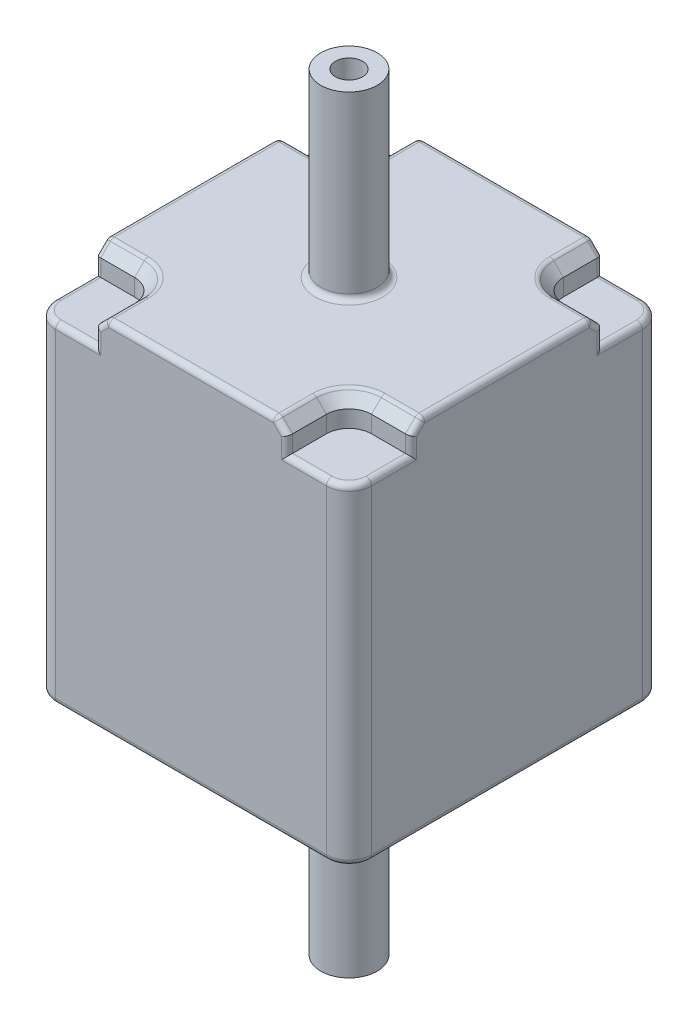
SolidWorks part; units mm, degrees
ref_plane "前视基准面" through (0, 0, 0) normal (0, 0, 1) x (1, 0, 0)
ref_plane "上视基准面" through (0, 0, 0) normal (0, 1, 0) x (1, 0, 0)
ref_plane "右视基准面" through (0, 0, 0) normal (1, 0, 0) x (0, 0, -1)
sketch "草图1" plane through (0, 0, 0) normal (0, 1, 0) x (1, 0, 0)
  line L1 (-14, 14) -> (14, 14)
  line L2 (-14, 14) -> (-14, -14)
  line L3 (-14, -14) -> (14, -14)
  line L4 (14, 14) -> (14, -14)
  point P4 (-14, 0)
  point P6 (0, 14)
  dimension "D1" = 28
  dimension "D2" = 28
extrude "凸台-拉伸1" add sketch "草图1" along normal blind 31.8
sketch "草图2" plane through (0, 0, 0) normal (0, -1, 0) x (-1, 0, 0)
  circle A0 centre (0, 0) radius 10.975
  dimension "D1" = 21.95
extrude "凸台-拉伸2" add sketch "草图2" along normal blind 2
sketch "草图3" plane through (0, -2, 0) normal (0, -1, 0) x (1, 0, 0)
  circle A0 centre (0, 0) radius 2.5
  dimension "D1" = 5
extrude "凸台-拉伸3" add sketch "草图3" along normal blind 18.2
sketch "草图4" plane through (0, 31.8, 0) normal (0, 1, 0) x (1, 0, 0)
  circle A0 centre (0, 0) radius 2.5
  dimension "D1" = 5
extrude "凸台-拉伸4" add sketch "草图4" along normal blind 16
fillet "圆角1" radius 2 4 edges at (14, 15.9, -14) (14, 15.9, 14) (-14, 15.9, -14) (-14, 15.9, 14)
sketch "草图5" plane through (0, 0, 0) normal (0, -1, 0) x (1, 0, 0)
  line L0 (-11.5, 11.5) -> (11.5, -11.5) construction
  circle A0 centre (-11.5, 11.5) radius 1.25
  circle A1 centre (11.5, 11.5) radius 1.25
  circle A2 centre (11.5, -11.5) radius 1.25
  circle A3 centre (-11.5, -11.5) radius 1.25
  point P8 (0, 0)
  point P9 (-14, -11.7456)
  point P11 (-7.5658, -11.5)
  point P12 (0, 0)
  point P13 (0, 0)
  point P14 (0, 0)
  point P15 (-14, -14)
  point P16 (9, 11.2897)
  point P17 (0, 0)
  point P18 (0, 0)
  dimension "D1" = 2.5
  dimension "D2" = 23
  dimension "D3" = 23
extrude "切除-拉伸1" cut sketch "草图5" against normal blind 5
sketch "草图6" plane through (0, 31.8, 0) normal (0, 1, 0) x (1, 0, 0)
  line L0 (-14, 12) -> (-14, -12) construction
  line L1 (-14, -8.5) -> (-10.5, -8.5)
  line L2 (-14, -8.5) -> (-14, -14)
  line L3 (-14, -14) -> (-8.5, -14)
  line L4 (-8.5, -10.5) -> (-8.5, -14)
  line L5 (-12, -14) -> (12, -14) construction
  line L6 (14, -12) -> (14, 12) construction
  line L7 (14, 8.5) -> (10.5, 8.5)
  line L8 (14, 8.5) -> (14, 14)
  line L9 (14, 14) -> (8.5, 14)
  line L10 (8.5, 10.5) -> (8.5, 14)
  line L11 (12, 14) -> (-12, 14) construction
  line L13 (-8.5, 14) -> (-14, 14)
  line L14 (-8.5, 14) -> (-8.5, 10.5)
  line L15 (-10.5, 8.5) -> (-14, 8.5)
  line L16 (-14, 14) -> (-14, 8.5)
  line L17 (14, -8.5) -> (10.5, -8.5)
  line L18 (14, -8.5) -> (14, -14)
  line L19 (14, -14) -> (8.5, -14)
  line L20 (8.5, -10.5) -> (8.5, -14)
  arc A0 (-10.5, -8.5) -> (-8.5, -10.5) centre (-10.5, -10.5) cw
  arc A1 (10.5, -8.5) -> (8.5, -10.5) centre (10.5, -10.5) ccw
  arc A2 (10.5, 8.5) -> (8.5, 10.5) centre (10.5, 10.5) cw
  arc A3 (-8.5, 10.5) -> (-10.5, 8.5) centre (-10.5, 10.5) cw
  point P24 (0, 0)
  point P27 (-8.5, -8.5)
  point P30 (8.5, -8.5)
  point P33 (8.5, 8.5)
  point P36 (-8.5, 8.5)
  dimension "D9" = 2
  dimension "D1" = 5.5
  dimension "D2" = 5.5
  dimension "D3" = 5.5
  dimension "D4" = 5.5
  dimension "D5" = 5.5
  dimension "D6" = 5.5
  dimension "D7" = 5.5
  dimension "D8" = 5.5
extrude "切除-拉伸2" cut sketch "草图6" against normal blind 2.5
chamfer "倒角1" distance 1 angle 45 12 edges at (12.25, 31.8, 8.5) (8.5, 31.8, 12.25) (9.0858, 31.8, 9.0858) (8.5, 31.8, -12.25) (12.25, 31.8, -8.5) (9.0858, 31.8, -9.0858) (-8.5, 31.8, 12.25) (-12.25, 31.8, 8.5) (-9.0858, 31.8, 9.0858) (-12.25, 31.8, -8.5) (-9.0858, 31.8, -9.0858) (-8.5, 31.8, -12.25)
fillet "圆角2" radius 0.5 53 edges at (13.4142, 29.3, 13.4142) (-13.4142, 29.3, 13.4142) (-13.4142, 29.3, -13.4142) (13.4142, 0, -13.4142) (13.4142, 0, 13.4142) (-13.4142, 0, 13.4142) (-13.4142, 0, -13.4142) (13.4142, 29.3, -13.4142) (0, 31.8, 2.5) (7.5, 31.8, 12.25) (-7.5, 31.8, 12.25) (-8.3787, 31.8, 8.3787) (-12.25, 31.8, 7.5) (-12.25, 31.8, -7.5) (-8.3787, 31.8, -8.3787) (-7.5, 31.8, -12.25) (7.5, 31.8, -12.25) (8.3787, 31.8, -8.3787) (12.25, 31.8, -7.5) (12.25, 31.8, 7.5) (8.3787, 31.8, 8.3787) (14, 31.3, -8) (14, 30.05, -8.5) (14, 29.3, -10.25) (14, 0, 0) (14, 29.3, 10.25) (14, 30.05, 8.5) (14, 31.3, 8) (14, 31.8, 0) (10.25, 29.3, 14) (0, 0, 14) (-10.25, 29.3, 14) (-8.5, 30.05, 14) (-8, 31.3, 14) (0, 31.8, 14) (8, 31.3, 14) (8.5, 30.05, 14) (-14, 29.3, 10.25) (-14, 0, 0) (-14, 29.3, -10.25) (-14, 30.05, -8.5) (-14, 31.3, -8) (-14, 31.8, 0) (-14, 31.3, 8) (-14, 30.05, 8.5) (-8, 31.3, -14) (-8.5, 30.05, -14) (-10.25, 29.3, -14) (0, 0, -14) (10.25, 29.3, -14) (8.5, 30.05, -14) (8, 31.3, -14) (0, 31.8, -14)
sketch "草图7" plane through (0, 47.8, 0) normal (0, 1, 0) x (1, 0, 0)
  circle A0 centre (0, 0) radius 1.2
  dimension "D1" = 2.4
extrude "切除-拉伸3" cut sketch "草图7" against normal through all
